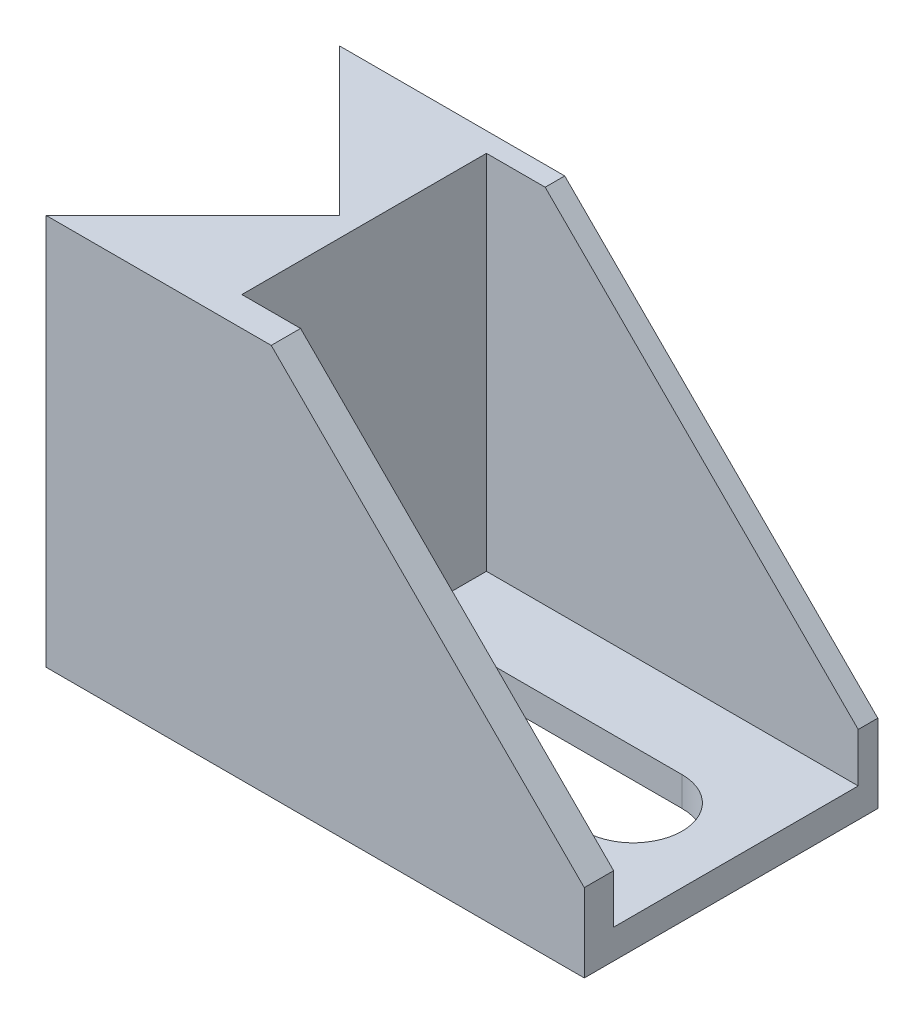
SolidWorks part; units mm, degrees
material "ABS"
ref_plane "Front Plane" through (0, 0, 0) normal (0, 0, 1) x (1, 0, 0)
ref_plane "Top Plane" through (0, 0, 0) normal (0, 1, 0) x (1, 0, 0)
ref_plane "Right Plane" through (0, 0, 0) normal (1, 0, 0) x (0, 0, -1)
sketch "Sketch1" plane through (0, 0, 0) normal (0, 0, 1) x (1, 0, 0)
  line L0 (0, 0) -> (25.4, 0)
  line L1 (25.4, 0) -> (25.4, 5.08)
  line L2 (25.4, 5.08) -> (5.08, 25.4)
  line L3 (5.08, 25.4) -> (0, 25.4)
  line L4 (0, 25.4) -> (0, 0)
  dimension "D1" = 25.4
  dimension "D2" = 5.08
extrude "Boss-Extrude1" add sketch "Sketch1" along normal blind 19.05
shell "Shell1" thickness 1.905
sketch "Sketch2" plane through (0, 0, 0) normal (0, -1, 0) x (1, 0, 0)
  line L0 (6.35, 9.525) -> (19.05, 9.525) construction
  line L1 (6.35, 12.7) -> (19.05, 12.7)
  line L2 (6.35, 6.35) -> (19.05, 6.35)
  line L4 (0, 19.05) -> (25.4, 19.05) construction
  line L5 (0, 19.05) -> (0, 0) construction
  arc A0 (6.35, 12.7) -> (6.35, 6.35) centre (6.35, 9.525) ccw
  arc A1 (19.05, 6.35) -> (19.05, 12.7) centre (19.05, 9.525) ccw
  point P2 (12.7, 9.525)
  point P7 (0, 0)
  point P9 (0, 0)
  point P11 (0, 0)
  point P12 (12.7, 19.05)
  point P13 (0, 0)
  point P16 (0, 9.525)
  dimension "D1" = 3.175
  dimension "D2" = 12.7
extrude "Cut-Extrude1" cut sketch "Sketch2" against normal up to surface (1.905 mm away) up to face at (12.7, 1.905, 9.525)
sketch "Sketch3" plane through (0, 25.4, 0) normal (0, 1, 0) x (1, 0, 0)
  line L0 (0, -9.525) -> (-9.525, 0)
  line L1 (0, -19.05) -> (0, 0) construction
  line L2 (-9.525, 0) -> (0, 0)
  line L3 (0, 0) -> (0, -19.05)
  line L4 (0, -19.05) -> (-9.525, -19.05)
  line L5 (-9.525, -19.05) -> (0, -9.525)
  line M5 (0, 0) -> (0, -19.05)
  dimension "D1" = 9.525
extrude "Boss-Extrude2" add sketch "Sketch3" against normal up to surface (25.4 mm away) contours L2 L0 M5 | L5 L4 M5 up to face at (12.7, 0, 9.525)
sketch "Sketch5" plane through (0, 25.4, 0) normal (0, 1, 0) x (1, 0, 0)
  line L0 (1.27, -1.27) -> (1.27, -17.145)
  line L3 (25.4, -1.27) -> (25.4, -17.145)
  line L4 (25.4, -19.05) -> (25.4, 0) construction
  line L5 (25.4, -17.145) -> (1.27, -17.145)
  line L6 (1.905, -17.145) -> (23.495, -17.145) construction
  line L7 (25.4, -1.27) -> (1.27, -1.27)
  dimension "D1" = 1.27
extrude "Cut-Extrude2" cut sketch "Sketch5" against normal up to surface (23.495 mm away)
